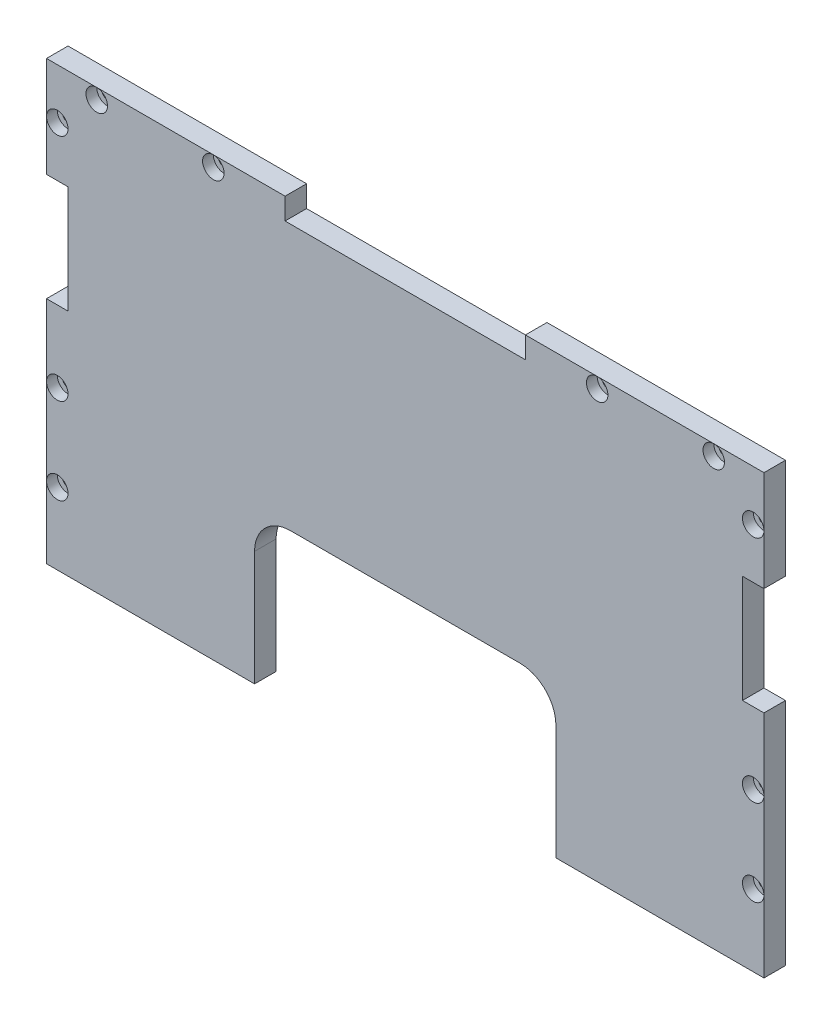
SolidWorks part; units mm, degrees
ref_plane "Plan de face" through (0, 0, 0) normal (0, 0, 1) x (1, 0, 0)
ref_plane "Plan de dessus" through (0, 0, 0) normal (0, 1, 0) x (1, 0, 0)
ref_plane "Plan de droite" through (0, 0, 0) normal (1, 0, 0) x (0, 0, -1)
sketch "Esquisse1" plane through (0, 0, 0) normal (0, 0, 1) x (1, 0, 0)
  line L1 (-96.6867, 51.3554) -> (103.3133, 51.3554)
  line L2 (-96.6867, 51.3554) -> (-96.6867, -70.6446)
  line L3 (-96.6867, -70.6446) -> (103.3133, -70.6446)
  line L4 (103.3133, 51.3554) -> (103.3133, -70.6446)
  dimension "D1" = 200
  dimension "D2" = 122
extrude "Boss.-Extru.1" add sketch "Esquisse1" along normal blind 6
sketch "Esquisse2" plane through (0, 0, 6) normal (0, 0, 1) x (1, 0, 0)
  line L0 (103.3133, 51.3554) -> (-96.6867, 51.3554) construction
  line L1 (-30.1867, 51.3554) -> (36.8133, 51.3554)
  line L2 (-30.1867, 51.3554) -> (-30.1867, 45.3554)
  line L3 (-30.1867, 45.3554) -> (36.8133, 45.3554)
  line L4 (36.8133, 51.3554) -> (36.8133, 45.3554)
  line L5 (-96.6867, 51.3554) -> (-96.6867, -70.6446) construction
  line L6 (103.3133, -70.6446) -> (103.3133, 51.3554) construction
  line L7 (-96.6867, 23.3554) -> (-90.6867, 23.3554)
  line L8 (-96.6867, 23.3554) -> (-96.6867, -6.6446)
  line L9 (-96.6867, -6.6446) -> (-90.6867, -6.6446)
  line L10 (-90.6867, 23.3554) -> (-90.6867, -6.6446)
  line L11 (103.3133, 23.3554) -> (97.3133, 23.3554)
  line L12 (103.3133, 23.3554) -> (103.3133, -6.6446)
  line L13 (103.3133, -6.6446) -> (97.3133, -6.6446)
  line L14 (97.3133, 23.3554) -> (97.3133, -6.6446)
  line L15 (-96.6867, -70.6446) -> (103.3133, -70.6446) construction
  line L16 (-38.6867, -70.6446) -> (45.3133, -70.6446)
  line L17 (-38.6867, -70.6446) -> (-38.6867, -28.6446)
  line L18 (-38.6867, -28.6446) -> (45.3133, -28.6446)
  line L19 (45.3133, -70.6446) -> (45.3133, -28.6446)
  dimension "D1" = 6
  dimension "D2" = 67
  dimension "D3" = 66.5
  dimension "D4" = 66.5
  dimension "D5" = 28
  dimension "D6" = 30
  dimension "D7" = 28
  dimension "D8" = 30
  dimension "D9" = 6
  dimension "D10" = 6
  dimension "D11" = 84
  dimension "D12" = 58
  dimension "D13" = 58
  dimension "D14" = 42
extrude "Enlèv. mat.-Extru.1" cut sketch "Esquisse2" against normal blind 6
fillet "Congé1" radius 10 2 edges at (45.3133, -28.6446, 3) (-38.6867, -28.6446, 3)
sketch "Esquisse3" plane through (0, 0, 6) normal (0, 0, 1) x (1, 0, 0)
  line L0 (-96.6867, -6.6446) -> (-96.6867, -70.6446) construction
  line L1 (-96.6867, 51.3554) -> (-96.6867, 23.3554) construction
  line L2 (-30.1867, 51.3554) -> (-96.6867, 51.3554) construction
  line L3 (103.3133, 23.3554) -> (103.3133, 51.3554) construction
  line L4 (103.3133, -70.6446) -> (103.3133, -6.6446) construction
  line L5 (-90.6867, 23.3554) -> (-96.6867, 23.3554) construction
  line L6 (-30.1867, 51.3554) -> (-30.1867, 45.3554) construction
  line L7 (36.8133, 45.3554) -> (36.8133, 51.3554) construction
  line L8 (103.3133, 23.3554) -> (97.3133, 23.3554) construction
  line L9 (97.3133, -6.6446) -> (103.3133, -6.6446) construction
  line L10 (45.3133, -70.6446) -> (103.3133, -70.6446) construction
  line L11 (-96.6867, -70.6446) -> (-38.6867, -70.6446) construction
  line L12 (-96.6867, -6.6446) -> (-90.6867, -6.6446) construction
  line L13 (103.3133, 51.3554) -> (36.8133, 51.3554) construction
  circle A0 centre (-93.6867, -50.6446) radius 1.5
  circle A1 centre (-93.6867, -26.6446) radius 1.5
  circle A2 centre (-93.6867, 37.3554) radius 1.5
  circle A3 centre (-50.1867, 48.3554) radius 1.5
  circle A4 centre (56.8133, 48.3554) radius 1.5
  circle A5 centre (100.3133, 37.3554) radius 1.5
  circle A6 centre (100.3133, -26.6446) radius 1.5
  circle A7 centre (100.3133, -50.6446) radius 1.5
  circle A8 centre (-82.6867, 48.3554) radius 1.5
  circle A9 centre (89.3133, 48.3554) radius 1.5
  point P26 (-93.6867, 23.3554)
  point P29 (-30.1867, 48.3554)
  dimension "D1" = 3
  dimension "D2" = 3
  dimension "D3" = 3
  dimension "D4" = 3
  dimension "D5" = 3
  dimension "D6" = 3
  dimension "D7" = 3
  dimension "D8" = 3
  dimension "D9" = 3
  dimension "D10" = 3
  dimension "D11" = 3
  dimension "D12" = 3
  dimension "D13" = 3
  dimension "D15" = 3
  dimension "D16" = 3
  dimension "D18" = 20
  dimension "D19" = 3
  dimension "D20" = 3
  dimension "D21" = 32.5
  dimension "D22" = 20
  dimension "D23" = 14
  dimension "D24" = 20
  dimension "D26" = 20
  dimension "D27" = 20
  dimension "D28" = 3
  dimension "D29" = 3
  dimension "D14" = 3
  dimension "D17" = 14
  dimension "D25" = 20
  dimension "D30" = 32.5
extrude "Enlèv. mat.-Extru.2" cut sketch "Esquisse3" against normal blind 6
sketch "Esquisse4" plane through (0, 0, 6) normal (0, 0, 1) x (1, 0, 0)
  circle A0 centre (-93.6867, -50.6446) radius 2.995
  circle A1 centre (-93.6867, -26.6446) radius 2.995
  circle A2 centre (-93.6867, 37.3554) radius 2.995
  circle A3 centre (-82.6867, 48.3554) radius 2.995
  circle A4 centre (-50.1867, 48.3554) radius 2.995
  circle A5 centre (56.8133, 48.3554) radius 2.995
  circle A6 centre (89.3133, 48.3554) radius 2.995
  circle A7 centre (100.3133, 37.3554) radius 2.995
  circle A8 centre (100.3133, -26.6446) radius 2.995
  circle A9 centre (100.3133, -50.6446) radius 2.995
  dimension "D1" = 5.99
  dimension "D2" = 5.99
  dimension "D3" = 5.99
  dimension "D4" = 5.99
  dimension "D5" = 5.99
  dimension "D6" = 5.99
  dimension "D7" = 5.99
  dimension "D8" = 5.99
  dimension "D9" = 5.99
  dimension "D10" = 5.99
extrude "Enlèv. mat.-Extru.3" cut sketch "Esquisse4" against normal blind 3
